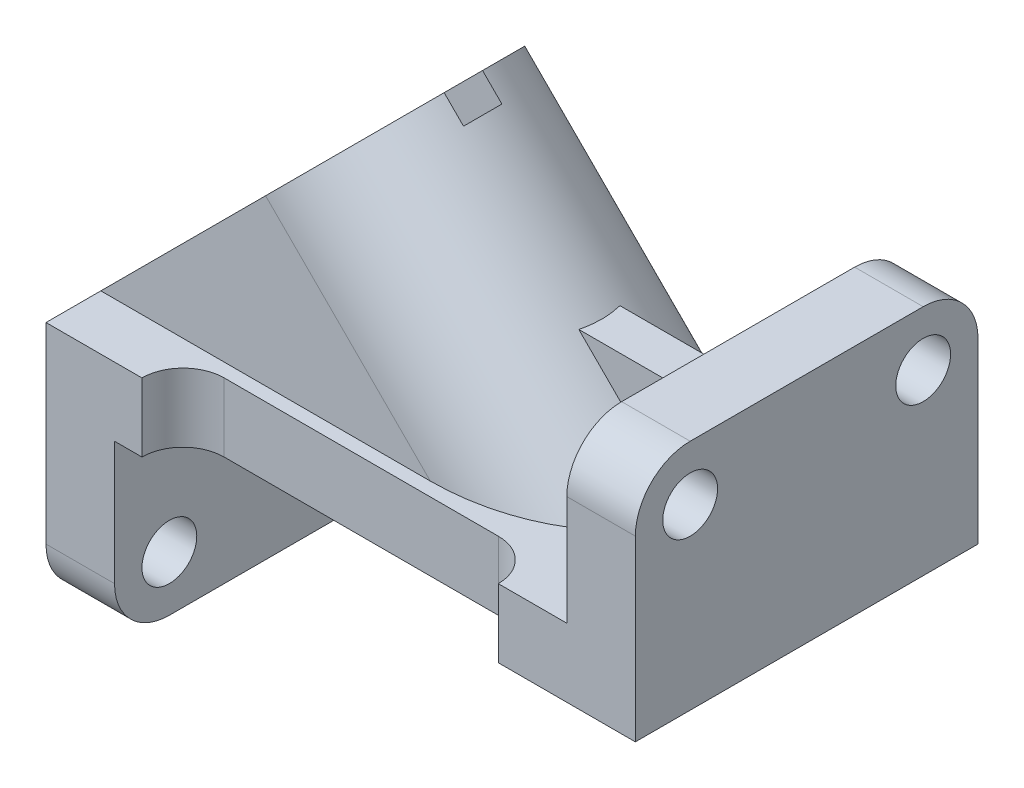
SolidWorks part; units mm, degrees
ref_plane "Front Plane" through (0, 0, 0) normal (0, 0, 1) x (1, 0, 0)
ref_plane "Top Plane" through (0, 0, 0) normal (0, 1, 0) x (1, 0, 0)
ref_plane "Right Plane" through (0, 0, 0) normal (1, 0, 0) x (0, 0, -1)
sketch "Sketch1" plane through (0, 0, 0) normal (0, 0, 1) x (1, 0, 0)
  line L0 (0, 0) -> (190, 0)
  line L1 (190, 0) -> (190, 85)
  line L2 (190, 85) -> (165, 85)
  line L3 (165, 85) -> (165, 25)
  line L4 (165, 25) -> (-25, 25)
  line L5 (-25, 25) -> (-25, -65)
  line L6 (-25, -65) -> (0, -65)
  line L7 (0, -65) -> (0, 0)
  point P8 (-25, -20)
  dimension "D1" = 215
  dimension "D2" = 25
  dimension "D3" = 25
  dimension "D4" = 25
  dimension "D5" = 85
  dimension "D6" = 90
extrude "Boss-Extrude1" add sketch "Sketch1" along normal mid plane 125
fillet "Fillet1" radius 20 4 edges at (-12.5, -65, -62.5) (-12.5, -65, 62.5) (177.5, 85, -62.5) (177.5, 85, 62.5)
sketch "Sketch2" plane through (190, 0, 0) normal (1, 0, 0) x (0, 0, -1)
  circle A0 centre (42.5, 65) radius 10
  circle A1 centre (-42.5, 65) radius 10
  arc A2 (62.5, 65) -> (42.5, 85) centre (42.5, 65) ccw construction
  arc A3 (-42.5, 85) -> (-62.5, 65) centre (-42.5, 65) ccw construction
  dimension "D1" = 20
  dimension "D2" = 20
extrude "Cut-Extrude1" cut sketch "Sketch2" against normal through all
sketch "Sketch3" plane through (-25, 0, 0) normal (-1, 0, 0) x (0, 0, 1)
  circle A0 centre (42.5, -45) radius 10
  circle A1 centre (-42.5, -45) radius 10
  arc A2 (42.5, -65) -> (62.5, -45) centre (42.5, -45) ccw construction
  arc A3 (-62.5, -45) -> (-42.5, -65) centre (-42.5, -45) ccw construction
  dimension "D1" = 20
  dimension "D2" = 20
extrude "Cut-Extrude2" cut sketch "Sketch3" against normal blind 125
sketch "Sketch4" plane through (0, 0, 0) normal (0, 0, 1) x (1, 0, 0)
  line L0 (165, 65) -> (16.9131, 65)
  line L1 (165, 65) -> (165, 25) construction
  line L2 (16.9131, 65) -> (16.9131, 25)
  line L3 (165, 25) -> (-25, 25) construction
  line L4 (16.9131, 25) -> (165, 25)
  line L5 (165, 25) -> (165, 65)
  dimension "D1" = 40
extrude "Boss-Extrude2" add sketch "Sketch4" along normal mid plane 15
ref_plane "Plane1" through (-25, 25, 0) normal (-0.7071, 0.7071, 0) x (0, 0, -1)
sketch "Sketch5" plane through (-25, 25, 0) normal (-0.7071, 0.7071, 0) x (0, 0, -1)
  line L0 (-42.5, 0) -> (-42.5, -85)
  line L1 (-62.5, 0) -> (62.5, 0) construction
  line L2 (42.5, -85) -> (42.5, 0)
  line L3 (42.5, 0) -> (-42.5, 0)
  arc A0 (-42.5, -85) -> (42.5, -85) centre (0, -85) ccw
  point P6 (0, 0)
  point P8 (0, 0)
  dimension "D1" = 85
  dimension "D2" = 85
extrude "Boss-Extrude3" add sketch "Sketch5" against normal up to next
sketch "Sketch7" plane through (0, 25, 0) normal (0, 1, 0) x (1, 0, 0)
  line L0 (165, -62.5) -> (-25, -62.5) construction
  line L1 (25, -47.5) -> (125, -47.5)
  line L2 (-25, -62.5) -> (-25, -42.5) construction
  line L3 (10, -62.5) -> (140, -62.5)
  arc A0 (25, -47.5) -> (10, -62.5) centre (25, -62.5) ccw
  arc A1 (140, -62.5) -> (125, -47.5) centre (125, -62.5) ccw
  dimension "D1" = 30
  dimension "D2" = 30
  dimension "D3" = 50
  dimension "D4" = 100
extrude "Cut-Extrude3" cut sketch "Sketch7" against normal up to next
mirror "Mirror1" about plane through (0, 0, 0) normal (0, 0, 1) of "Cut-Extrude3"
sketch "Sketch8" plane through (-25, 25, 0) normal (-0.7071, 0.7071, 0) x (0, 0, 1)
  line L0 (0, 0) -> (0, 130.9943) construction
  line L1 (-7, -26.7402) -> (-7, 126.9196)
  line L3 (7, -26.7402) -> (7, 126.9196)
  line L4 (-7, -26.7402) -> (7, -26.7402)
  arc A1 (7, 126.9196) -> (-7, 126.9196) centre (0, 85) ccw
  arc A2 (42.5, 85) -> (-42.5, 85) centre (0, 85) ccw construction
  point P4 (0, 130.9943)
  point P5 (0, 0)
  point P6 (0, 0)
  point P9 (-7, 50.0897)
  point P12 (0, 0)
  point P13 (-7.5, 128.6005)
  point P17 (-7, 0)
  dimension "D1" = 7
extrude "Cut-Extrude4" cut sketch "Sketch8" against normal blind 10
hole_wizard "CBORE for M24 Hex Head Bolt2" positions "Sketch12" profile "Sketch13" counterbore size "M24" standard "ANSI Metric" end condition through all
sketch "Sketch12" plane through (-25, 25, 0) normal (-0.7071, 0.7071, 0) x (0, 0, 1)
  line L0 (-42.5, 0) -> (-7, 0) construction
  line L1 (0, -98.8601) -> (0, 98.8601) construction
  point P0 (0, 85)
  dimension "D1" = 85
  dimension "D2" = 0
sketch "Sketch13" plane through (35.1041, 85.1041, 0) normal (0, 0, 1) x (-0.7071, -0.7071, 0)
  line L0 (0, 0) -> (0, 215.6676)
  line L1 (0, 215.6676) -> (13, 215.6676)
  line L3 (13, 215.6676) -> (13, 15.9)
  line L4 (22.285, 15.9) -> (13, 15.9)
  line L5 (22.285, 15.9) -> (22.285, 0.025)
  line L6 (22.285, 0.025) -> (22.31, 0)
  line L7 (22.31, 0) -> (0, 0)
  line L8 (-22.285, 0.025) -> (-22.31, 0) construction
  line L11 (0, -6.35) -> (0, 107.95) construction
  dimension "Thru Hole Dia." = 26
  dimension "Thru Hole Depth" = 215.6676
  dimension "C'Bore Dia." = 44.57
  dimension "C'Bore Depth" = 15.9
  dimension "Near C'Sink Dia." = 44.62
  dimension "Near C'Sink Angle" = 90
